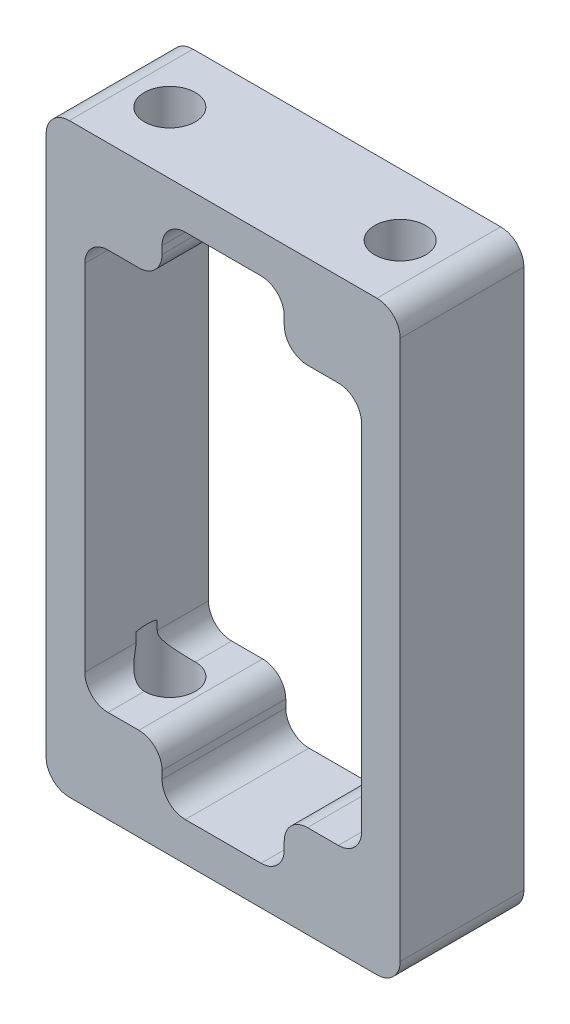
SolidWorks part; units mm, degrees
material "6061 合金"
ref_plane "前视基准面" through (0, 0, 0) normal (0, 0, 1) x (1, 0, 0)
ref_plane "上视基准面" through (0, 0, 0) normal (0, 1, 0) x (1, 0, 0)
ref_plane "右视基准面" through (0, 0, 0) normal (1, 0, 0) x (0, 0, -1)
other "Configuration Table"
sketch "草图1" plane through (0, 0, 0) normal (0, 0, 1) x (1, 0, 0)
  line L1 (-11.45, -18.95) -> (11.45, -18.95)
  line L2 (-11.45, -18.95) -> (-11.45, 18.95)
  line L3 (-11.45, 18.95) -> (11.45, 18.95)
  line L4 (11.45, -18.95) -> (11.45, 18.95)
  line L5 (-11.45, -18.95) -> (11.45, 18.95) construction
  line L6 (-11.45, 18.95) -> (11.45, -18.95) construction
  point P0 (0, 0)
  dimension "D1" = 37.9
  dimension "D2" = 22.9
extrude "凸台-拉伸1" add sketch "草图1" along normal mid plane 8
sketch "草图3" plane through (0, 18.95, 0) normal (0, 1, 0) x (1, 0, 0)
  line L0 (-7.45, 0) -> (7.45, 0) construction
  line L1 (11.45, -4) -> (11.45, 4) construction
  point P4 (0, 0)
  dimension "D1" = 4
hole_wizard "M4 螺纹孔1" positions "草图4" profile "草图5" tap size "M4" standard "GB"
sketch "草图4" plane through (0, 18.95, 0) normal (0, 1, 0) x (1, 0, 0)
  point P0 (-7.45, 0)
  point P3 (7.45, 0)
cosmetic thread "孔螺蚊线1" parameters "D1"=6, "D2"=4
cosmetic thread "孔螺蚊线2" parameters "D1"=6, "D2"=4
sketch "草图5" plane through (-7.45, 18.95, 0) normal (1, 0, 0) x (0, 0, 1)
  line L0 (0, 0) -> (0, 9.0914)
  line L1 (0, 9.0914) -> (1.65, 8.1)
  line L2 (1.65, 8.1) -> (1.65, 0)
  line L5 (1.65, 0) -> (0, 0)
  line L10 (0, 9.0914) -> (-1.65, 8.1) construction
  line L11 (0, -6.35) -> (0, 107.95) construction
  dimension "螺纹孔钻头直径" = 3.3
  dimension "螺纹孔钻头深度" = 8.1
  dimension "导头角度" = 118
mirror "镜向1" about plane through (0, 0, 0) normal (0, 1, 0) of "M4 螺纹孔1"
sketch "草图6" plane through (0, 0, 4) normal (0, 0, 1) x (1, 0, 0)
  line L0 (-7.45, 18.95) -> (7.45, 18.95) construction
  line L1 (-8.95, -12.95) -> (8.95, -12.95)
  line L2 (-8.95, -12.95) -> (-8.95, 12.95)
  line L3 (-8.95, 12.95) -> (8.95, 12.95)
  line L4 (8.95, -12.95) -> (8.95, 12.95)
  line L5 (-8.95, -12.95) -> (8.95, 12.95) construction
  line L6 (-8.95, 12.95) -> (8.95, -12.95) construction
  line L7 (11.45, -18.95) -> (11.45, 18.95) construction
  point P0 (0, 0)
  dimension "D1" = 6
  dimension "D2" = 2.5
extrude "切除-拉伸1" cut sketch "草图6" against normal mid plane 38
sketch "草图7" plane through (0, 0, 4) normal (0, 0, 1) x (1, 0, 0)
  line L0 (-7.45, 18.95) -> (7.45, 18.95) construction
  line L1 (-3.95, -16.45) -> (3.95, -16.45)
  line L2 (-3.95, -16.45) -> (-3.95, 16.45)
  line L3 (-3.95, 16.45) -> (3.95, 16.45)
  line L4 (3.95, -16.45) -> (3.95, 16.45)
  line L5 (-3.95, -16.45) -> (3.95, 16.45) construction
  line L6 (-3.95, 16.45) -> (3.95, -16.45) construction
  line L7 (8.95, 12.95) -> (8.95, -12.95) construction
  point P0 (0, 0)
  dimension "D1" = 2.5
  dimension "D2" = 5
extrude "切除-拉伸2" cut sketch "草图7" against normal mid plane 38
fillet "圆角1" radius 1.5 16 edges at (-8.95, 12.95, -2.3437) (8.95, -12.95, 2.3437) (8.95, 12.95, 2.3437) (3.95, 12.95, 0) (-3.95, 12.95, 0) (-8.95, 12.95, 2.3437) (3.95, -12.95, 0) (-8.95, -12.95, 2.3437) (-8.95, -12.95, -2.3437) (-3.95, -12.95, 0) (3.95, -16.45, 0) (-3.95, -16.45, 0) (3.95, 16.45, 0) (8.95, 12.95, -2.3437) (8.95, -12.95, -2.3437) (-3.95, 16.45, 0)
fillet "圆角2" radius 1.5 4 edges at (11.45, -18.95, 0) (-11.45, -18.95, 0) (-11.45, 18.95, 0) (11.45, 18.95, 0)
